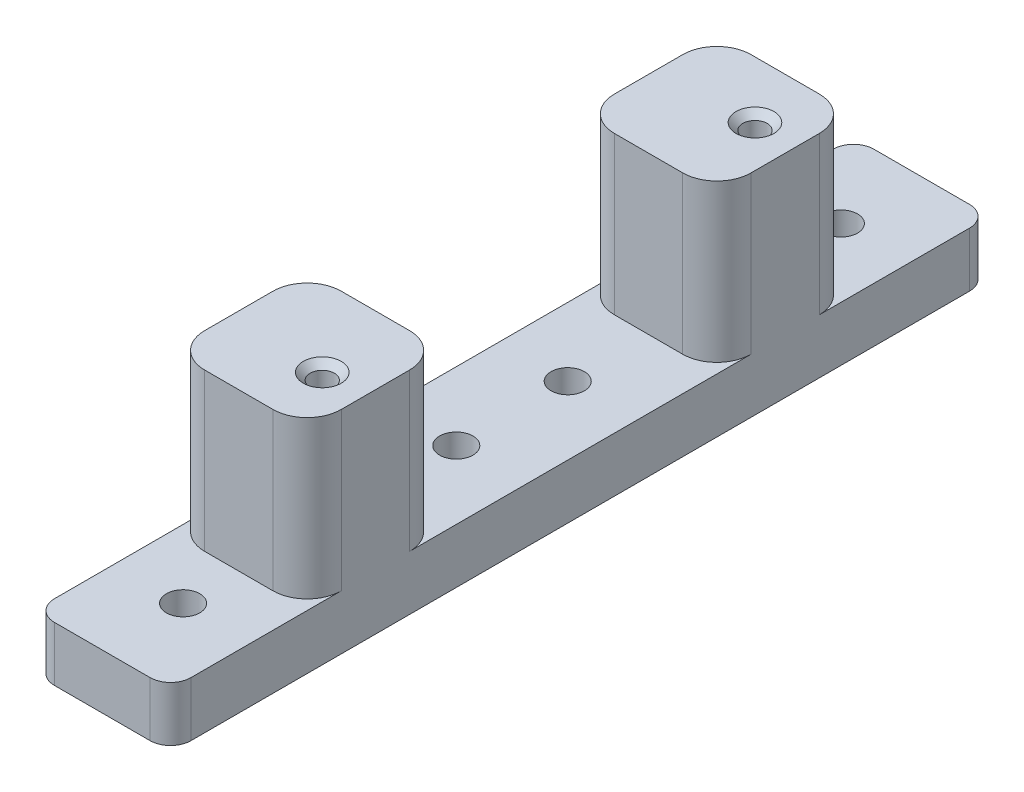
SolidWorks part; units mm, degrees
ref_plane "Front Plane" through (0, 0, 0) normal (0, 0, 1) x (1, 0, 0)
ref_plane "Top Plane" through (0, 0, 0) normal (0, 1, 0) x (1, 0, 0)
ref_plane "Right Plane" through (0, 0, 0) normal (1, 0, 0) x (0, 0, -1)
sketch "Sketch1" plane through (0, 0, 0) normal (0, 1, 0) x (1, 0, 0)
  line L1 (-5, -30) -> (5, -30)
  line L2 (-5, -30) -> (-5, 30)
  line L3 (-5, 30) -> (5, 30)
  line L4 (5, -30) -> (5, 30)
  line L5 (-5, -30) -> (5, 30) construction
  line L6 (-5, 30) -> (5, -30) construction
  point P0 (0, 0)
  dimension "D1" = 10
  dimension "D2" = 60
extrude "Boss-Extrude1" add sketch "Sketch1" along normal blind 4
sketch "Sketch2" plane through (0, 4, 0) normal (0, 1, 0) x (1, 0, 0)
  line L0 (0, -4.08) -> (0, 4.08) construction
  line L1 (0, 4.08) -> (0, 24.08) construction
  line L4 (0, -4.08) -> (0, -24.08) construction
  point P0 (0, -4.08)
  point P4 (0, 0)
  point P7 (0, 24.08)
  point P8 (0, 4.08)
  point P11 (0, -24.08)
  dimension "D1" = 20
  dimension "D2" = 8.16
hole_wizard "#2 Clearance Hole1" positions "Sketch2" profile "Sketch3" hole size "#2" standard "ANSI Inch"
sketch "Sketch3" plane through (0, 4, 4.08) normal (1, 0, 0) x (0, 0, 1)
  line L0 (0, 0) -> (0, 4)
  line L1 (0, 4) -> (1.2192, 4)
  line L2 (1.2192, 4) -> (1.2192, 0)
  line L5 (1.2192, 0) -> (0, 0)
  line L11 (0, -6.35) -> (0, 107.95) construction
  dimension "Thru Hole Dia." = 2.4384
  dimension "Thru Hole Depth" = 4
fillet "Fillet1" radius 1.5 4 edges at (-5, 2, -30) (5, 2, -30) (-5, 2, 30) (5, 2, 30)
sketch "Sketch4" plane through (0, 4, 0) normal (0, 1, 0) x (1, 0, 0)
  line L0 (-5, 28.5) -> (-5, -28.5) construction
  line L1 (-5, -10) -> (5, -10)
  line L2 (-5, -10) -> (-5, -20)
  line L3 (-5, -20) -> (5, -20)
  line L4 (5, -10) -> (5, -20)
  line L5 (5, -28.5) -> (5, 28.5) construction
  line L6 (-3.5, -30) -> (3.5, -30) construction
  dimension "D1" = 10
  dimension "D2" = 10
extrude "Boss-Extrude2" add sketch "Sketch4" along normal blind 11.5
fillet "Fillet2" radius 2.5 4 edges at (-5, 9.75, 10) (5, 9.75, 10) (-5, 9.75, 20) (5, 9.75, 20)
sketch "Sketch5" plane through (0, 15.5, 0) normal (0, 1, 0) x (1, 0, 0)
  line L0 (0, -24.08) -> (0, -15.84) construction
  line L1 (0, -15.84) -> (1.95, -15.84) construction
  point P6 (1.95, -15.84)
  dimension "D1" = 8.24
  dimension "D2" = 1.95
hole_wizard "Tap Drill for #2-56 Tap1" positions "Sketch5" profile "Sketch6" hole size "#2-56" standard "ANSI Inch"
sketch "Sketch6" plane through (1.95, 15.5, 15.84) normal (1, 0, 0) x (0, 0, 1)
  line L0 (0, 0) -> (0, 10.6942)
  line L1 (0, 10.6942) -> (0.889, 10.16)
  line L2 (0.889, 10.16) -> (0.889, 0)
  line L5 (0.889, 0) -> (0, 0)
  line L10 (0, 10.6942) -> (-0.889, 10.16) construction
  line L11 (0, -6.35) -> (0, 107.95) construction
  dimension "Hole Dia." = 1.778
  dimension "Hole Depth" = 10.16
  dimension "Drill Angle" = 118
chamfer "Chamfer1" distance 0.5 angle 45 1 edges at (1.95, 15.5, 16.729)
ref_plane "Plane1" through (0, 0, 0) normal (0, 0, 1) x (1, 0, 0)
mirror "Mirror1" about plane through (0, 0, 0) normal (0, 0, 1) of "Chamfer1", "Tap Drill for #2-56 Tap1", "Fillet2", "Boss-Extrude2"
